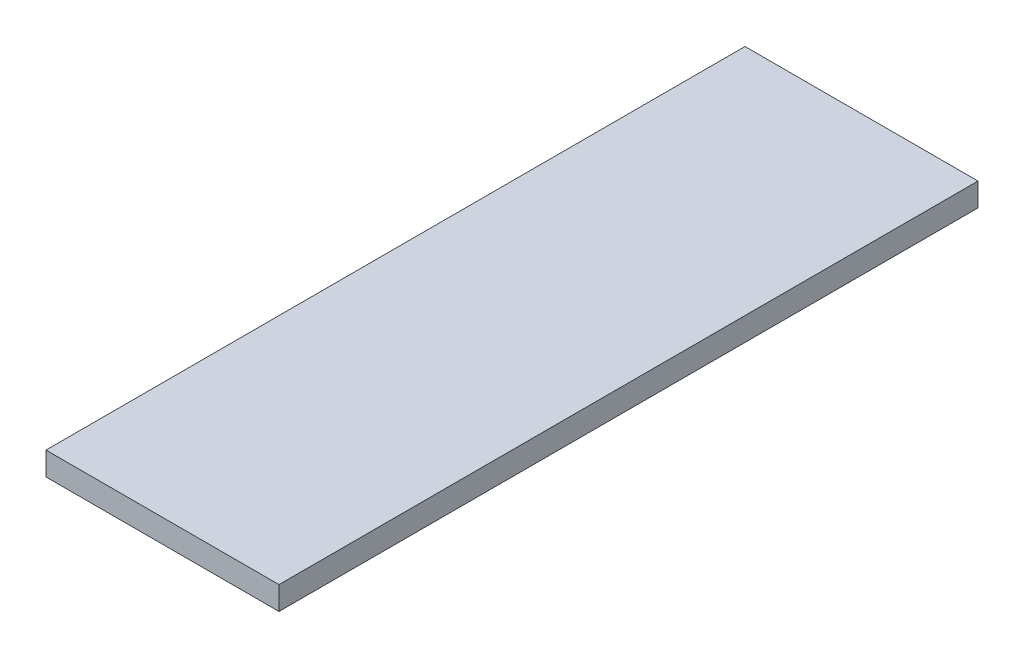
SolidWorks part; units mm, degrees
ref_plane "Спереди" through (0, 0, 0) normal (0, 0, 1) x (1, 0, 0)
ref_plane "Сверху" through (0, 0, 0) normal (0, 1, 0) x (1, 0, 0)
ref_plane "Справа" through (0, 0, 0) normal (1, 0, 0) x (0, 0, -1)
sketch "Эскиз1" plane through (0, 0, 0) normal (0, 1, 0) x (1, 0, 0)
  line L1 (0, 0) -> (100, 0)
  line L2 (0, 0) -> (0, 300)
  line L3 (0, 300) -> (100, 300)
  line L4 (100, 0) -> (100, 300)
  dimension "D1" = 100
  dimension "D2" = 300
extrude "Нижняя панель каретки" add sketch "Эскиз1" along normal blind 10
